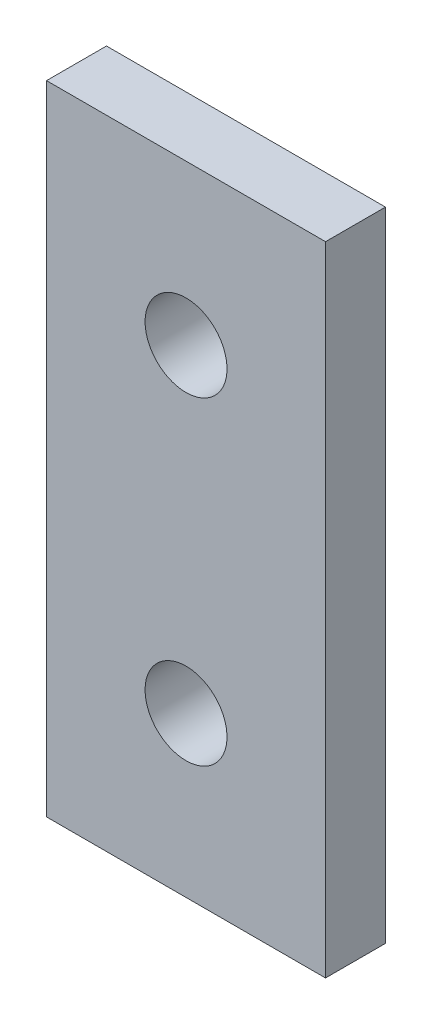
SolidWorks part; units mm, degrees
ref_plane "Front Plane" through (0, 0, 0) normal (0, 0, 1) x (1, 0, 0)
ref_plane "Top Plane" through (0, 0, 0) normal (0, 1, 0) x (1, 0, 0)
ref_plane "Right Plane" through (0, 0, 0) normal (1, 0, 0) x (0, 0, -1)
ref_plane "Plane1" through (0, 0, 4.7752) normal (0, 0, 1) x (1, 0, 0)
sketch "Sketch1" plane through (0, 0, 4.7752) normal (0, 0, 1) x (1, 0, 0)
  line L0 (11.1125, 50.8) -> (-11.1125, 50.8)
  line L1 (-11.1125, 50.8) -> (-11.1125, 0)
  line L2 (-11.1125, 0) -> (11.1125, 0)
  line L3 (11.1125, 0) -> (11.1125, 50.8)
  circle A0 centre (0, 38.1) radius 3.2639
  circle A1 centre (0, 12.7) radius 3.2639
extrude "Boss-Extrude1" add sketch "Sketch1" against normal blind 4.7752
